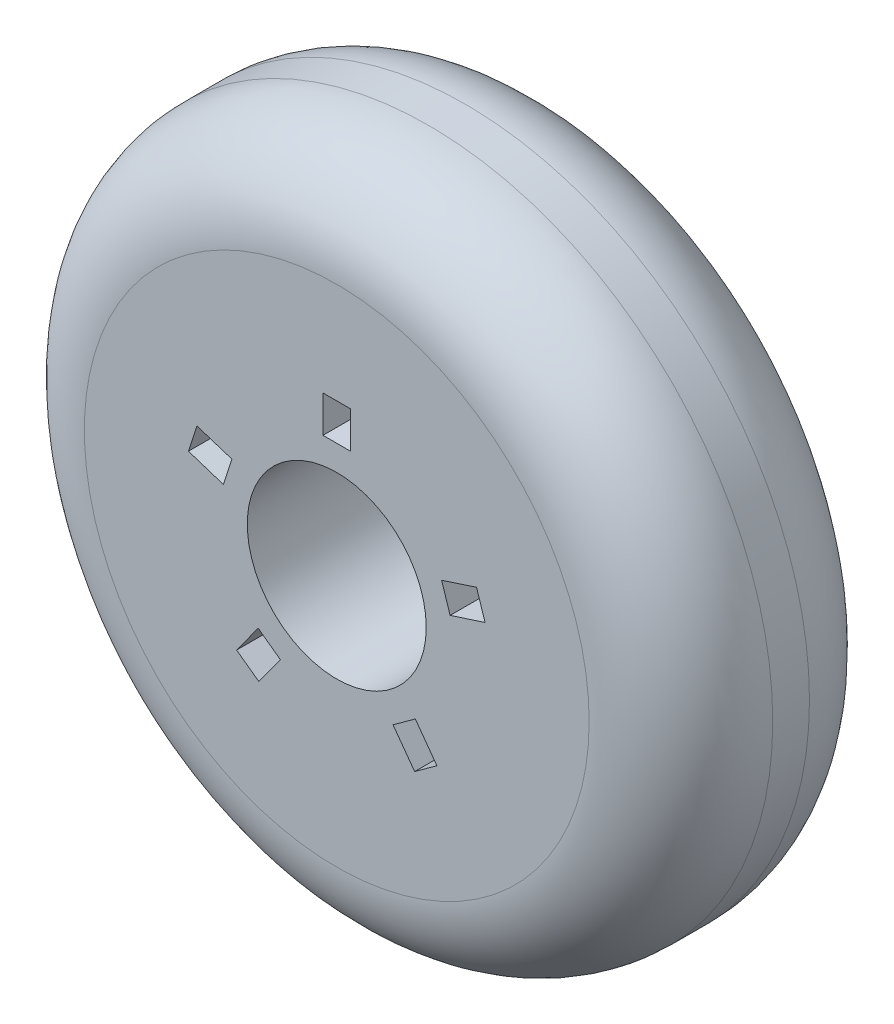
SolidWorks part; units mm, degrees
ref_plane "Plan de face" through (0, 0, 0) normal (0, 0, 1) x (1, 0, 0)
ref_plane "Plan de dessus" through (0, 0, 0) normal (0, 1, 0) x (1, 0, 0)
ref_plane "Plan de droite" through (0, 0, 0) normal (1, 0, 0) x (0, 0, -1)
sketch "Esquisse1" plane through (0, 0, 0) normal (0, 0, 1) x (1, 0, 0)
  circle A0 centre (0, 0) radius 37.5
  circle A1 centre (0, 0) radius 9.75
  dimension "D1" = 75
  dimension "D2" = 19.5
extrude "Boss.-Extru.1" add sketch "Esquisse1" along normal blind 24
fillet "Congé1" radius 10 2 edges at (37.5, 0, 0) (37.5, 0, 24)
sketch "Esquisse3" plane through (0, 0, 24) normal (0, 0, 1) x (1, 0, 0)
  line L0 (15.2289, 6.5254) -> (16.156, 3.6722)
  line L1 (-1.5, 16.5) -> (1.5, 16.5)
  line L2 (-1.5, 16.5) -> (-1.5, 12.5)
  line L3 (-1.5, 12.5) -> (1.5, 12.5)
  line L4 (1.5, 16.5) -> (1.5, 12.5)
  line L5 (15.2289, 6.5254) -> (11.4247, 5.2893)
  line L6 (16.156, 3.6722) -> (12.3517, 2.4361)
  line L7 (11.4247, 5.2893) -> (12.3517, 2.4361)
  line L8 (10.912, -12.4671) -> (8.4849, -14.2305)
  line L9 (10.912, -12.4671) -> (8.5608, -9.231)
  line L10 (8.4849, -14.2305) -> (6.1338, -10.9944)
  line L11 (8.5608, -9.231) -> (6.1338, -10.9944)
  line L12 (-8.4849, -14.2305) -> (-10.912, -12.4671)
  line L13 (-8.4849, -14.2305) -> (-6.1338, -10.9944)
  line L14 (-10.912, -12.4671) -> (-8.5608, -9.231)
  line L15 (-6.1338, -10.9944) -> (-8.5608, -9.231)
  line L16 (-16.156, 3.6722) -> (-15.2289, 6.5254)
  line L17 (-16.156, 3.6722) -> (-12.3517, 2.4361)
  line L18 (-15.2289, 6.5254) -> (-11.4247, 5.2893)
  line L19 (-12.3517, 2.4361) -> (-11.4247, 5.2893)
  point P4 (0, 12.5)
  point P25 (0, 0)
  dimension "D1" = 4
  dimension "11.68" = 12.5
  dimension "D2" = 3
  dimension "D3" = 1.5
  dimension "D4" = 5
extrude "Enlèv. mat.-Extru.1" cut sketch "Esquisse3" against normal through all
